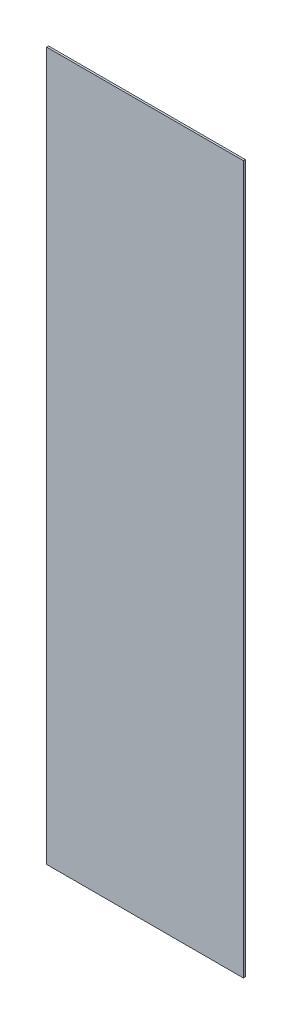
SolidWorks part; units mm, degrees
ref_plane "Front Plane" through (0, 0, 0) normal (0, 0, 1) x (1, 0, 0)
ref_plane "Top Plane" through (0, 0, 0) normal (0, 1, 0) x (1, 0, 0)
ref_plane "Right Plane" through (0, 0, 0) normal (1, 0, 0) x (0, 0, -1)
sketch "Sketch1" plane through (0, 0, 0) normal (0, 0, 1) x (1, 0, 0)
  line L1 (0, 0) -> (254, 0)
  line L2 (0, 0) -> (0, 914.4)
  line L3 (0, 914.4) -> (254, 914.4)
  line L4 (254, 0) -> (254, 914.4)
  line L5 (0, 0) -> (254, 914.4) construction
  line L6 (0, 914.4) -> (254, 0) construction
  point P4 (127, 457.2)
  dimension "D1" = 254
  dimension "D2" = 914.4
extrude "Boss-Extrude1" add sketch "Sketch1" along normal blind 2.54
